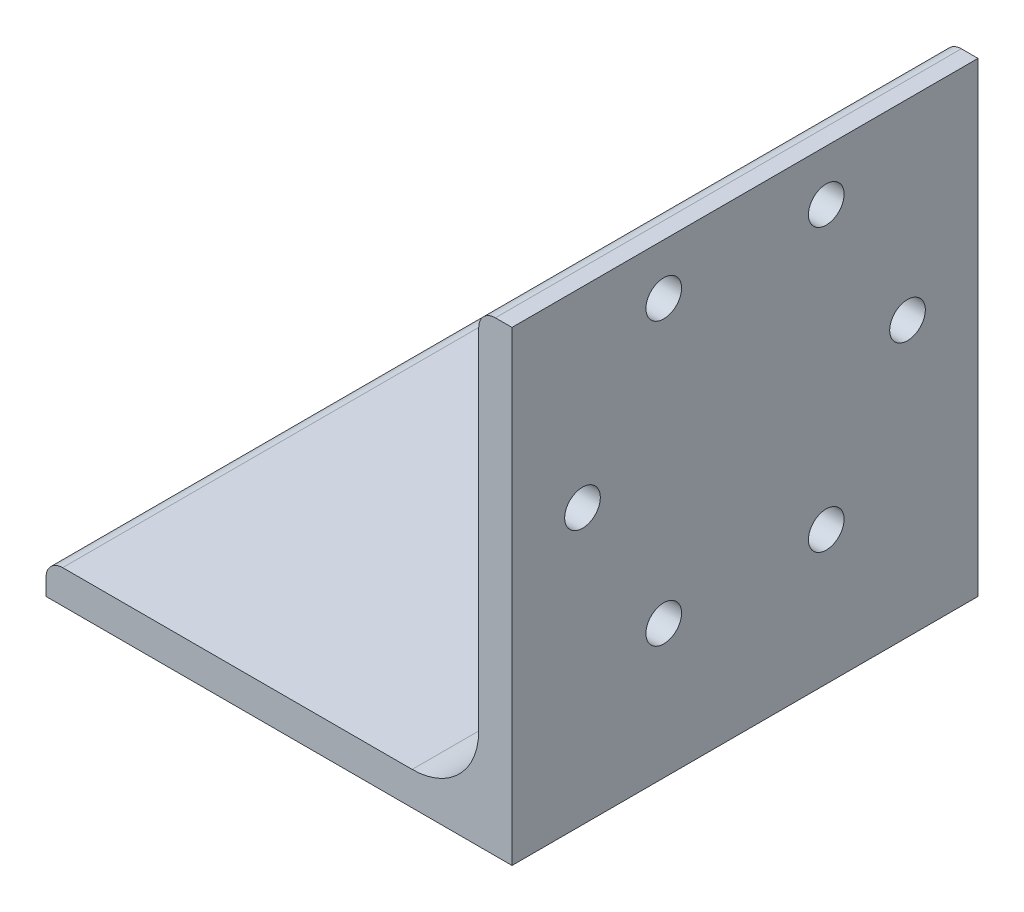
SolidWorks part; units mm, degrees
ref_plane "Front Plane" through (0, 0, 0) normal (0, 0, 1) x (1, 0, 0)
ref_plane "Top Plane" through (0, 0, 0) normal (0, 1, 0) x (1, 0, 0)
ref_plane "Right Plane" through (0, 0, 0) normal (1, 0, 0) x (0, 0, -1)
sketch "Sketch2" plane through (0, 0, 0) normal (0, 0, 1) x (1, 0, 0)
  line L0 (-22.225, 0) -> (22.225, 0)
  line L1 (22.225, 0) -> (22.225, 44.45)
  line L2 (22.225, 44.45) -> (19.05, 44.45) construction
  line L3 (19.05, 42.8625) -> (19.05, 9.525)
  line L4 (12.7, 3.175) -> (-20.6375, 3.175)
  line L5 (-22.225, 0) -> (-22.225, 3.175) construction
  line L6 (20.6375, 44.45) -> (22.225, 44.45)
  line L7 (-22.225, 1.5875) -> (-22.225, 0)
  arc A0 (19.05, 42.8625) -> (20.6375, 44.45) centre (20.6375, 42.8625) cw
  arc A1 (-22.225, 1.5875) -> (-20.6375, 3.175) centre (-20.6375, 1.5875) cw
  arc A2 (19.05, 9.525) -> (12.7, 3.175) centre (12.7, 9.525) cw
  dimension "Inside Radius" = 6.35
  dimension "Vert" = 44.45
  dimension "Horz" = 44.45
  dimension "Thickness" = 3.175
extrude "Boss-Extrude1" add sketch "Sketch2" along normal mid plane 44.45
sketch "Break Locations" plane through (0, 0, 0) normal (1, 0, 0) x (0, 0, -1)
  line L1 (-22.225, 0) -> (-22.225, 44.45) construction
  line L2 (22.225, 0) -> (22.225, 44.45) construction
  point P0 (15.5575, 0)
  point P1 (-15.5575, 0)
  dimension "D1" = 37.7825
  dimension "D2" = 37.7825
ref_plane "Contact Plane 1" through (0, 3.175, 0) normal (0, 1, 0) x (1, 0, 0)
ref_plane "Contact Plane 2" through (19.05, 0, 0) normal (-1, 0, 0) x (0, 0, 1)
hole_wizard "M3 Clearance Hole1" positions "Sketch8" profile "Sketch10" hole size "M3" standard "ANSI Metric"
sketch "Sketch8" plane through (19.05, 0, 0) normal (-1, 0, 0) x (0, 0, 1)
  line L0 (22.225, 9.525) -> (-22.225, 9.525) construction
  line L1 (-13, 12.7) -> (13, 12.7) construction
  point P0 (-13, 38.7)
  point P2 (13, 38.7)
  point P4 (-13, 12.7)
  point P6 (13, 12.7)
  point P19 (0, 12.7)
  point P20 (0, 9.525)
  dimension "D1" = 3.175
  dimension "D2" = 26
  dimension "D3" = 26
sketch "Sketch10" plane through (19.05, 38.7, -13) normal (0, 1, 0) x (0, 0, 1)
  line L0 (0, 0) -> (0, 3.175)
  line L1 (0, 3.175) -> (1.7, 3.175)
  line L2 (1.7, 3.175) -> (1.7, 0)
  line L5 (1.7, 0) -> (0, 0)
  line L11 (0, -6.35) -> (0, 107.95) construction
  dimension "Thru Hole Dia." = 3.4
  dimension "Thru Hole Depth" = 3.175
hole_wizard "M3 Clearance Hole2" positions "Sketch13" profile "Sketch12" hole size "M3" standard "ANSI Metric" end condition through all
sketch "Sketch13" plane through (19.05, 0, 0) normal (-1, 0, 0) x (0, 0, 1)
  line L1 (15.5, 26.1937) -> (7.75, 39.6171) construction
  line L2 (7.75, 39.6171) -> (-7.75, 39.6171) construction
  line L3 (-7.75, 39.6171) -> (-15.5, 26.1937) construction
  line L4 (-15.5, 26.1937) -> (-7.75, 12.7704) construction
  line L5 (-7.75, 12.7704) -> (7.75, 12.7704) construction
  line L6 (7.75, 12.7704) -> (15.5, 26.1937) construction
  line L7 (22.225, 42.8625) -> (-22.225, 42.8625) construction
  line L8 (22.225, 42.8625) -> (22.225, 9.525) construction
  circle A0 centre (0, 26.1937) radius 13.4234 construction
  point P3 (15.5, 26.1937)
  point P4 (7.75, 39.6171)
  point P5 (-7.75, 39.6171)
  point P6 (-15.5, 26.1937)
  point P7 (-7.75, 12.7704)
  point P8 (7.75, 12.7704)
  point P14 (0, 42.8625)
  point P17 (22.225, 26.1937)
  dimension "D1" = 15.5
sketch "Sketch12" plane through (19.05, 12.7704, 7.75) normal (0, 1, 0) x (0, 0, 1)
  line L0 (0, 0) -> (0, 3.175)
  line L1 (0, 3.175) -> (1.7, 3.175)
  line L2 (1.7, 3.175) -> (1.7, 0)
  line L5 (1.7, 0) -> (0, 0)
  line L11 (0, -6.35) -> (0, 107.95) construction
  dimension "Thru Hole Dia." = 3.4
  dimension "Thru Hole Depth" = 3.175
equation "\"D1@Break Locations\"=.85*\"Vert@Sketch2\""
equation "\"D2@Break Locations\"=\"D1@Break Locations\""
